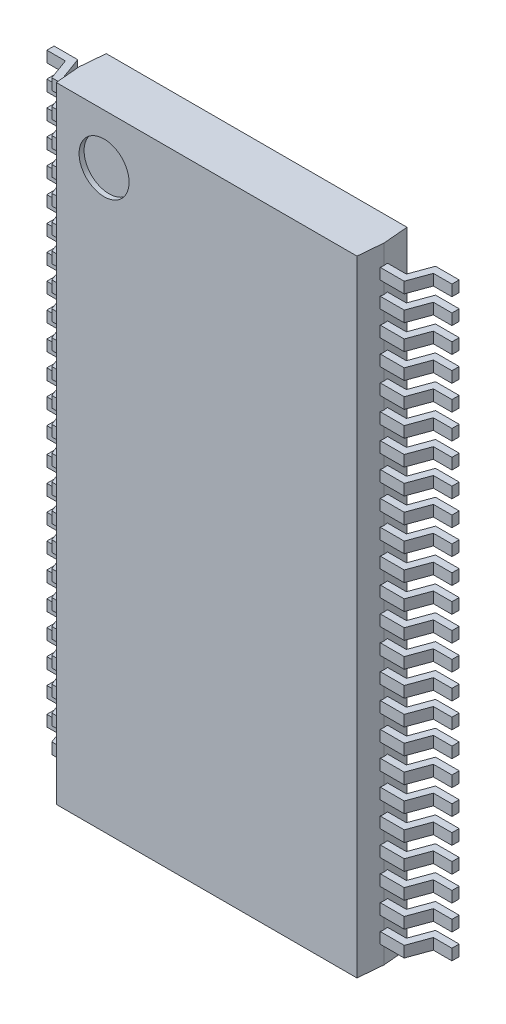
SolidWorks part; units mm, degrees
ref_plane "Front" through (0, 0, 0) normal (0, 0, 1) x (1, 0, 0)
ref_plane "Top" through (0, 0, 0) normal (0, 1, 0) x (1, 0, 0)
ref_plane "Right" through (0, 0, 0) normal (1, 0, 0) x (0, 0, -1)
sketch "Sketch1" plane through (0, 0, 0) normal (0, 1, 0) x (1, 0, 0)
  line L0 (-3.05, -0.5) -> (3.05, -0.5) construction
  line L1 (0, -1) -> (0, 0) construction
  line L2 (-3.05, -0.5) -> (-3.0063, -1)
  line L3 (-3.0063, -1) -> (3.0063, -1)
  line L4 (3.0063, -1) -> (3.05, -0.5)
  line L5 (3.05, -0.5) -> (3.0063, 0)
  line L6 (3.0063, 0) -> (-3.0063, 0)
  line L7 (-3.0063, 0) -> (-3.05, -0.5)
  point P5 (0, -0.5)
  point P9 (0, 0)
  point P11 (0, 0)
  point P12 (0, -0.3151)
  point P13 (0, 0)
  dimension "D1" = 6.1
  dimension "D2" = 1
  dimension "D3" = 85
extrude "Body" add sketch "Sketch1" along normal mid plane 12.5
sketch "Sketch3" plane through (0, 0, 1) normal (0, 0, 1) x (1, 0, 0)
  line L0 (-2.05, 6.25) -> (-2.05, 5.25) construction
  line L1 (-3.0063, 6.25) -> (3.0063, 6.25) construction
  line L2 (-2.05, 5.25) -> (-3.05, 5.25) construction
  line L3 (-3.05, 6.25) -> (-3.05, -6.25) construction
  circle A0 centre (-2.05, 5.25) radius 0.5
  dimension "D1" = 1
  dimension "D2" = 1
extrude "Pin 1 Mark" cut sketch "Sketch3" against normal blind 0.1
sketch "Sketch2" plane through (0, 6.25, 0) normal (0, 1, 0) x (1, 0, 0)
  line L0 (-3.0063, -0.5) -> (-3.05, -0.5)
  line L1 (-3.05, -0.5) -> (-3.4722, -0.5)
  line L2 (-3.4722, -0.5) -> (-3.6278, -0.0725)
  line L3 (-3.6278, -0.0725) -> (-4.05, -0.0725)
  line L4 (3.0063, 0) -> (-3.0063, 0) construction
  line L5 (-3.0063, -0.5) -> (-3.0063, 0) construction
  line L7 (0, 0) -> (0, -1) construction
  line L8 (-3.0063, -1) -> (3.0063, -1) construction
  line L9 (3.6278, -0.0725) -> (4.05, -0.0725)
  line L10 (3.4722, -0.5) -> (3.6278, -0.0725)
  line L11 (3.05, -0.5) -> (3.4722, -0.5)
  line L12 (3.0063, -0.5) -> (3.05, -0.5)
  dimension "D3" = 110
  dimension "D1" = 0.0725
  dimension "D2" = 8.1
extrude "Lead Profile" add sketch "Sketch2" against normal blind 0.22 from offset 0.39 thin thin type mid plane wall 0.145 offset against normal yes
pattern_linear "Leads" count 24 spacing 0.5 along (0, -1, 0) of "Lead Profile"
equation "\"D1@Sketch1\"=\"Body Width\""
equation "\"D2@Sketch1\"=\"Body Thickness\""
equation "\"D1@Body\" = \"Body Length\""
equation "\"D19@Lead Profile\" = \"Pin 1 Offset\" - \"Pin Width\" / 2"
equation "\"D1@Lead Profile\" = \"Pin Width\""
equation "\"D5@Lead Profile\" = \"Pin Thickness\""
equation "\"D3@Leads\"=\"Pin Pitch\""
equation "\"D1@Leads\"=\"Pin QTY\"/2"
equation "\"D1@Sketch2\"=\"Pin Thickness\"/2"
equation "\"D2@Sketch2\"=\"Overall Width\""
